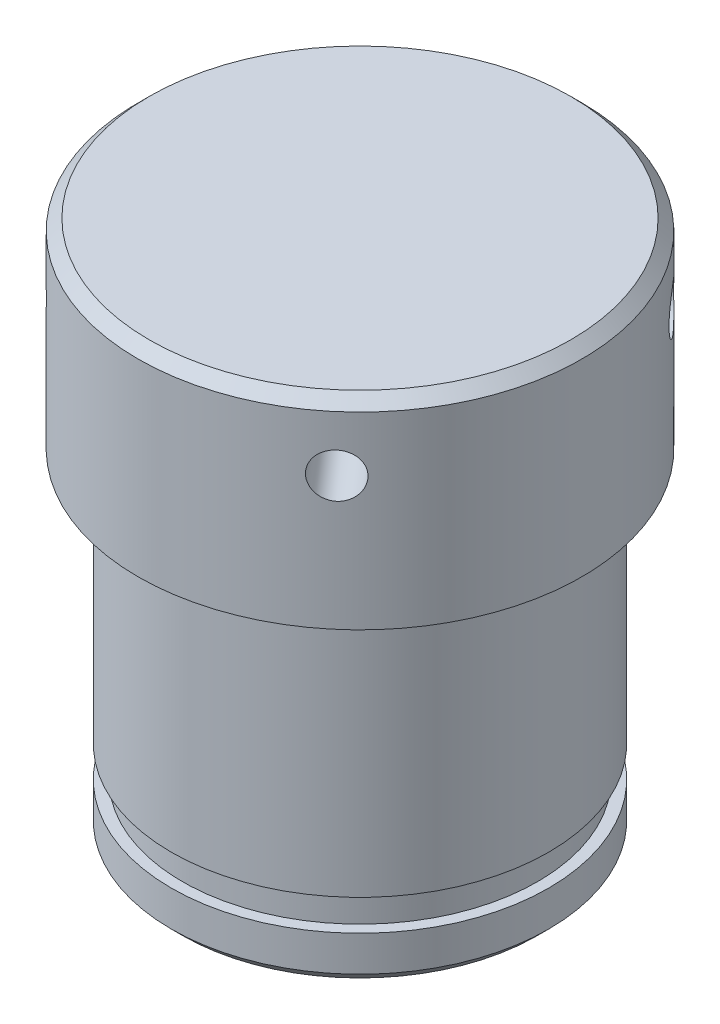
SolidWorks part; units mm, degrees
material "ABS"
ref_plane "Спереди" through (0, 0, 0) normal (0, 0, 1) x (1, 0, 0)
ref_plane "Сверху" through (0, 0, 0) normal (0, 1, 0) x (1, 0, 0)
ref_plane "Справа" through (0, 0, 0) normal (1, 0, 0) x (0, 0, -1)
sketch "Эскиз1" plane through (0, 0, 0) normal (0, 1, 0) x (1, 0, 0)
  circle A0 centre (0, 0) radius 8.5
  dimension "D1" = 17
extrude "Бобышка-Вытянуть1" add sketch "Эскиз1" along normal blind 15
sketch "Эскиз2" plane through (0, 15, 0) normal (0, 1, 0) x (1, 0, 0)
  circle A0 centre (0, 0) radius 10
  dimension "D1" = 20
extrude "Бобышка-Вытянуть2" add sketch "Эскиз2" along normal blind 9
sketch "Эскиз3" plane through (0, 0, 0) normal (0, -1, 0) x (1, 0, 0)
  circle A0 centre (0, 6) radius 1
  circle A1 centre (6, 0) radius 1
  circle A2 centre (0, -6) radius 1
  circle A3 centre (-6, 0) radius 1
  point P12 (0, 0)
  dimension "D1" = 2
  dimension "D2" = 6
  dimension "D3" = 4
extrude "Вырез-Вытянуть1" cut sketch "Эскиз3" against normal blind 10
sketch "Эскиз4" plane through (0, 0, 0) normal (0, -1, 0) x (1, 0, 0)
  circle A0 centre (0, 0) radius 8
  circle A1 centre (0, 0) radius 8.5
  dimension "D1" = 16
extrude "Вырез-Вытянуть2" cut sketch "Эскиз4" against normal blind 1.4 from offset 2.1 offset against normal yes
chamfer "Фаска1" distance 0.5 angle 45 2 edges at (0, 0, 8.5) (0, 24, 10)
sketch "Эскиз6" plane through (0, 24, 0) normal (0, 1, 0) x (1, 0, 0)
  line L0 (0, 12.2337) -> (0, -13.1957) construction
ref_plane "Плоскость1" through (6.5246, 0, 7.5782) normal (0.6525, 0, 0.7578) x (0.7578, 0, -0.6525)
sketch "Эскиз7" plane through (6.5246, 0, 7.5782) normal (0.6525, 0, 0.7578) x (0.7578, 0, -0.6525)
  line L0 (7.982, 24) -> (-8.6096, 24) construction
  circle A0 centre (0, 21) radius 1
  dimension "D1" = 2
  dimension "D2" = 3
extrude "Вырез-Вытянуть3" cut sketch "Эскиз7" against normal blind 8
pattern_circular "Круговой массив1" count 4 over 360 about axis through (0, 0, 0) along (0, 1, 0) of "Вырез-Вытянуть3"
